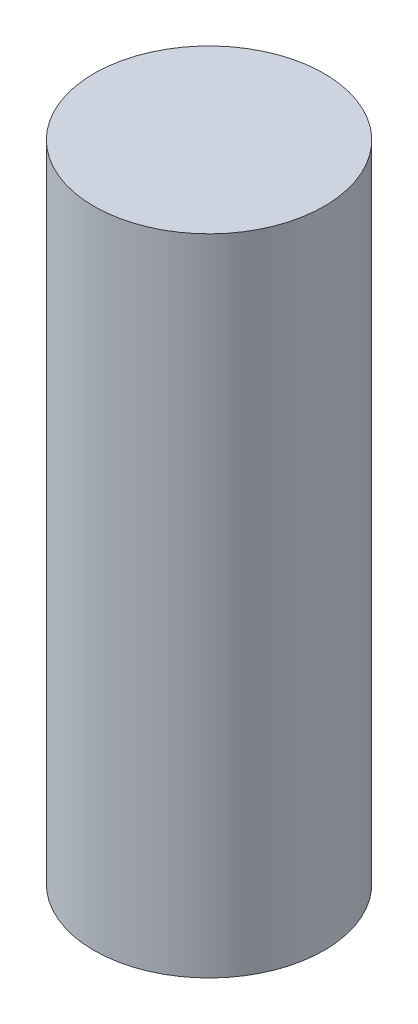
SolidWorks part; units mm, degrees
ref_plane "Front Plane" through (0, 0, 0) normal (0, 0, 1) x (1, 0, 0)
ref_plane "Top Plane" through (0, 0, 0) normal (0, 1, 0) x (1, 0, 0)
ref_plane "Right Plane" through (0, 0, 0) normal (1, 0, 0) x (0, 0, -1)
sketch "Sketch1" plane through (0, 0, 0) normal (0, 1, 0) x (1, 0, 0)
  circle A0 centre (0, 0) radius 2.5
  dimension "D1" = 5
extrude "Boss-Extrude1" add sketch "Sketch1" along normal blind 14
